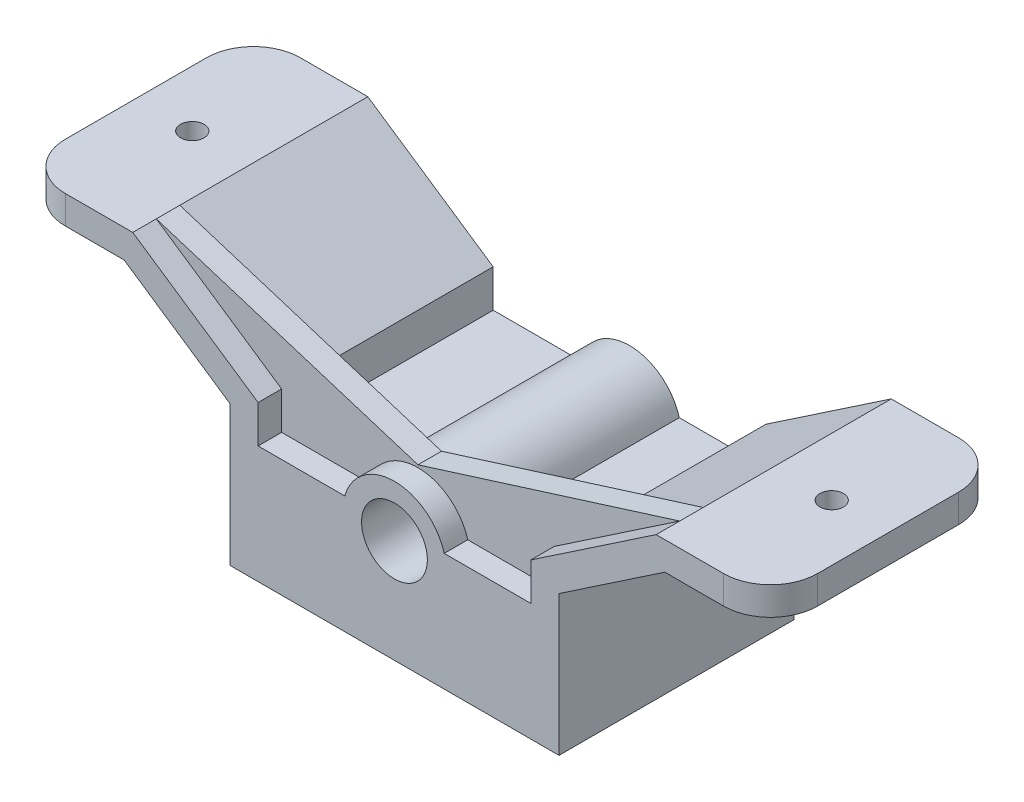
SolidWorks part; units mm, degrees
ref_plane "Front Plane" through (0, 0, 0) normal (0, 0, 1) x (1, 0, 0)
ref_plane "Top Plane" through (0, 0, 0) normal (0, 1, 0) x (1, 0, 0)
ref_plane "Right Plane" through (0, 0, 0) normal (1, 0, 0) x (0, 0, -1)
sketch "Sketch1" plane through (0, 0, 0) normal (0, 0, 1) x (1, 0, 0)
  line L0 (-35, 0) -> (-35, 29.8112)
  line L1 (-35, 29.8112) -> (-57.5, 45)
  line L2 (-57.5, 45) -> (-80, 45)
  line L3 (-80, 45) -> (-80, 51)
  line L4 (-80, 51) -> (-55.6644, 51)
  line L5 (-55.6644, 51) -> (-29, 33)
  line L6 (-29, 33) -> (-29, 25)
  line L7 (-29, 25) -> (-10.583, 25)
  line L8 (0, -55) -> (0, 55) construction
  line L9 (29, 25) -> (10.583, 25)
  line L10 (29, 33) -> (29, 25)
  line L11 (55.6644, 51) -> (29, 33)
  line L12 (80, 51) -> (55.6644, 51)
  line L13 (80, 45) -> (80, 51)
  line L14 (57.5, 45) -> (80, 45)
  line L15 (35, 29.8112) -> (57.5, 45)
  line L16 (35, 0) -> (35, 29.8112)
  line L17 (0, 0) -> (0, 66.332) construction
  line L18 (-35, 0) -> (35, 0)
  arc A0 (-10.583, 25) -> (10.583, 25) centre (0, 22) cw
  dimension "D1" = 11
  dimension "D2" = 51
  dimension "D3" = 6
  dimension "D4" = 70
  dimension "D5" = 58
  dimension "D6" = 22.5
  dimension "D7" = 22
  dimension "D8" = 25
  dimension "D9" = 8
  dimension "D10" = 6
  dimension "D11" = 160
extrude "Boss-Extrude1" add sketch "Sketch1" along normal mid plane 50
sketch "Sketch2" plane through (0, 0, 25) normal (0, 0, 1) x (1, 0, 0)
  line L0 (55.6644, 51) -> (29, 33) construction
  line L1 (29, 33) -> (29, 25) construction
  line L2 (29, 25) -> (10.583, 25) construction
  line L3 (-10.583, 25) -> (-29, 25) construction
  line L4 (-29, 25) -> (-29, 33) construction
  line L5 (-29, 33) -> (-55.6644, 51) construction
  line L6 (55.6644, 51) -> (29, 33)
  line L7 (29, 33) -> (29, 25)
  line L8 (29, 25) -> (10.583, 25)
  line L9 (-10.583, 25) -> (-29, 25)
  line L10 (-29, 25) -> (-29, 33)
  line L11 (-29, 33) -> (-55.6644, 51)
  line L12 (-55.6644, 51) -> (0, 33.5291)
  line L13 (55.6644, 51) -> (0, 33.5291)
  arc A0 (10.583, 25) -> (-10.583, 25) centre (0, 22) ccw construction
  arc A1 (10.583, 25) -> (-10.583, 25) centre (0, 22) ccw
extrude "Boss-Extrude3" add sketch "Sketch2" against normal blind 5 from offset 5 offset against normal yes
hole_wizard "Hole1" positions "Sketch3" profile "Sketch4" legacy end condition through all
sketch "Sketch3" plane through (0, 0, 25) normal (0, 0, 1) x (1, 0, 0)
  point P0 (0, 22)
sketch "Sketch4" plane through (0, 22, 25) normal (1, 0, 0) x (0, -1, 0)
  line L0 (0, 0) -> (0, 50)
  line L1 (0, 50) -> (7, 50)
  line L2 (7, 50) -> (7, 0)
  line L3 (7, 0) -> (0, 0)
  line L4 (0, 110) -> (0, -10) construction
  dimension "Diameter" = 14
  dimension "Depth" = 50
hole_wizard "Hole2" positions "Sketch5" profile "Sketch6" legacy end condition through all
sketch "Sketch5" plane through (0, 51, 0) normal (0, 1, 0) x (1, 0, 0)
  line L0 (80, -25) -> (80, 25) construction
  line L1 (80, -25) -> (55.6644, -25) construction
  point P0 (68, 0)
  point P9 (80, -6.6491)
  dimension "D1" = 12
  dimension "D2" = 25
sketch "Sketch6" plane through (68, 51, 0) normal (1, 0, 0) x (0, 0, 1)
  line L0 (0, 0) -> (0, 51)
  line L1 (0, 51) -> (2.5, 51)
  line L2 (2.5, 51) -> (2.5, 0)
  line L3 (2.5, 0) -> (0, 0)
  line L4 (0, 110) -> (0, -10) construction
  dimension "Diameter" = 5
  dimension "Depth" = 51
mirror "Mirror1" about plane through (0, 0, 0) normal (1, 0, 0) of "Hole2"
fillet "Fillet1" radius 10 4 edges at (-80, 48, 25) (-80, 48, -25) (80, 48, -25) (80, 48, 25)
